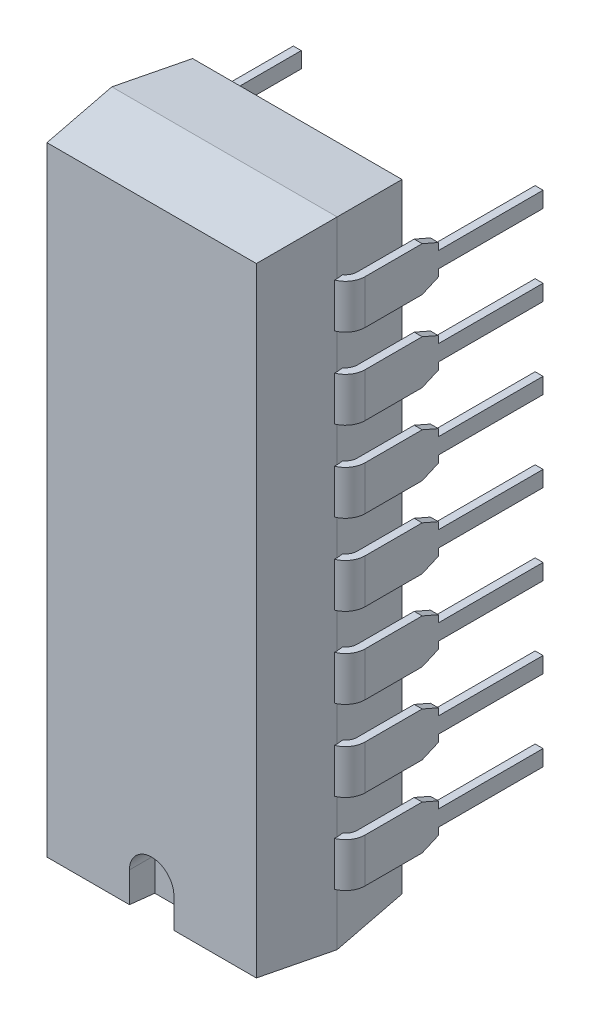
SolidWorks part; units mm, degrees
ref_plane "Plane1" through (0, 0, 0) normal (0, 0, 1) x (1, 0, 0)
ref_plane "Plane2" through (0, 0, 0) normal (0, 1, 0) x (1, 0, 0)
ref_plane "Plane3" through (0, 0, 0) normal (1, 0, 0) x (0, 0, -1)
sketch "Sketch1" plane through (0, 0, 0) normal (0, 1, 0) x (1, 0, 0)
  line L0 (-3.3, -5.1) -> (-3.55, -2.805)
  line L1 (-3.55, -2.805) -> (3.55, -2.805) construction
  line L2 (3.55, -2.805) -> (3.3, -5.1)
  line L3 (3.3, -5.1) -> (-3.3, -5.1)
  line L4 (-3.55, -2.805) -> (-3.3, -0.51)
  line L5 (-3.3, -0.51) -> (3.3, -0.51)
  line L6 (3.3, -0.51) -> (3.55, -2.805)
  line L7 (0, 0) -> (3.3, 0) construction
  line L8 (0, -0.51) -> (0, -5.1) construction
  point P11 (0, -2.805)
  point P12 (0, -5.1)
  point P13 (0, -0.51)
  dimension "D1" = 7.1
  dimension "D2" = 0.51
  dimension "D3" = 5.1
  dimension "D4" = 6.6
extrude "Basic Shape" add sketch "Sketch1" along normal mid plane 20
sketch "Sketch2" plane through (0, 0, 0) normal (1, 0, 0) x (0, 0, -1)
  line L1 (-0.51, -10) -> (-2.805, -10) construction
  line L2 (-0.51, 10) -> (-0.51, -10) construction
  line L3 (-0.51, 10) -> (-0.51, 9.75)
  line L4 (-0.51, 10) -> (-2.805, 10) construction
  line L5 (-0.51, 10) -> (-2.805, 10)
  line L6 (-2.805, 10) -> (-0.51, 9.75)
  line L7 (-0.51, -10) -> (-2.805, -10)
  line L9 (-2.805, -10) -> (-0.51, -9.75)
  line L11 (-0.51, -9.75) -> (-0.51, -10)
  dimension "D1" = 0.25
extrude "Side Profile1" cut sketch "Sketch2" against normal through all and the other way through all
sketch "Sketch3" plane through (0, 0, 0) normal (1, 0, 0) x (0, 0, -1)
  line L0 (-2.805, 10) -> (-5.1, 10) construction
  line L1 (-2.805, 10) -> (-5.1, 10)
  line L2 (-5.1, 10) -> (-5.1, -10) construction
  line L3 (-5.1, 10) -> (-5.1, 9.75)
  line L4 (-2.805, 10) -> (-5.1, 9.75)
  line L5 (-2.805, -10) -> (-5.1, -10) construction
  line L6 (-2.805, -10) -> (-5.1, -10)
  line L7 (-2.805, -10) -> (-5.1, -9.75)
  line L8 (-5.1, -9.75) -> (-5.1, -10)
extrude "Side Profile2" cut sketch "Sketch3" against normal through all and the other way through all
sketch "Sketch4" plane through (0, 0, 5.1) normal (0, 0, 1) x (1, 0, 0)
  line L2 (-0.7, -10) -> (-0.7, -8.8)
  line L3 (0.7, -8.8) -> (0.7, -10)
  line L4 (-3.55, -10) -> (3.55, -10) construction
  line L5 (-0.7, -10) -> (0.7, -10)
  arc A0 (-0.7, -8.8) -> (0.7, -8.8) centre (0, -8.8) cw
  dimension "D1" = 1.2
  dimension "D2" = 1.4
extrude "Location Mark" cut sketch "Sketch4" against normal blind 0.8
sketch "Sketch5" plane through (0, 0, 0) normal (0, 1, 0) x (1, 0, 0)
  line L0 (-3.55, -2.805) -> (3.55, -2.805) construction
  line L1 (0, -2.805) -> (3.31, -2.805)
  line L2 (3.81, -2.305) -> (3.81, 3.3)
  line L3 (3.81, -2.805) -> (-3.81, -2.805) construction
  arc A0 (3.81, -2.305) -> (3.31, -2.805) centre (3.31, -2.305) cw
  point P0 (-3.81, -2.805)
  point P8 (0, -2.805)
  dimension "D3" = 0.5
  dimension "D1" = 7.62
  dimension "D2" = 3.3
sketch "Sketch6" plane through (0, 0, 0) normal (1, 0, 0) x (0, 0, -1)
  line L0 (-2.93, 0.695) -> (-2.68, 0.695)
  line L1 (-2.93, 0.695) -> (-2.93, -0.695)
  line L2 (-2.68, -0.695) -> (-2.93, -0.695)
  line L3 (-2.68, -0.695) -> (-2.68, 0.695)
  line L4 (-2.68, 0.695) -> (-2.93, -0.695) construction
  point P4 (-2.805, 0)
  dimension "D1" = 1.39
  dimension "D2" = 0.25
sweep "Central Pin" add profiles "Sketch6" path "Sketch5"
sketch "Sketch7" plane through (3.685, 0, 0) normal (-1, 0, 0) x (0, 0, 1)
  line L0 (-3.3, -0.695) -> (-3.3, 0.695) construction
  line L1 (2.305, -0.695) -> (-3.3, -0.695) construction
  line L2 (-3.3, -0.25) -> (-3.3, 0.25) construction
  line L3 (-3.3, -0.25) -> (0, -0.25)
  line L4 (50, 0) -> (-50, 0) construction
  line L5 (-3.3, 0.25) -> (0, 0.25)
  line L6 (0, 0.25) -> (0, 0.4725)
  line L7 (0, -0.25) -> (0, -0.4725)
  line L8 (2.305, 0.695) -> (-3.3, 0.695) construction
  line L9 (0.51, 0.695) -> (-3.3, 0.695)
  line L10 (2.305, -0.695) -> (-3.3, -0.695) construction
  line L11 (0.51, -0.695) -> (-3.3, -0.695)
  line L12 (-3.3, -0.25) -> (-3.3, -0.695)
  line L13 (-3.3, 0.695) -> (-3.3, 0.25)
  line L14 (0, -0.4725) -> (0.51, -0.695)
  line L16 (0, 0.4725) -> (0.51, 0.695)
  line L17 (2.305, 0.695) -> (-3.3, 0.695) construction
  line L18 (0.51, 9.75) -> (0.51, -9.75) construction
  point P6 (-3.3, 0)
  point P10 (-3.3, 0.4725)
  dimension "D1" = 0.5
extrude "Pin Relief" cut sketch "Sketch7" against normal through all
mirror "Opp Pin" about plane through (0, 0, 0) normal (1, 0, 0) of "Pin Relief", "Central Pin"
pattern_linear "Upper Pins" count 4 spacing 2.54 along (0, -1, 0) of "Central Pin", "Opp Pin", "Pin Relief"
pattern_linear "Lower Pins" count 4 spacing 2.54 along (0, 1, 0) of "Pin Relief", "Opp Pin", "Central Pin"
sketch "Component_Outline" plane through (0, 0, 0) normal (0, 0, 1) x (1, 0, 0)
  line L0 (3.55, 10) -> (3.55, 8.315)
  line L1 (3.55, 8.315) -> (3.935, 8.315)
  line L2 (3.935, 8.315) -> (3.935, 6.925)
  line L3 (3.935, 6.925) -> (3.55, 6.925)
  line L4 (3.55, 6.925) -> (3.55, 5.775)
  line L5 (3.55, 5.775) -> (3.935, 5.775)
  line L6 (3.935, 5.775) -> (3.935, 4.385)
  line L7 (3.935, 4.385) -> (3.55, 4.385)
  line L8 (3.55, 4.385) -> (3.55, 3.235)
  line L9 (3.55, 3.235) -> (3.935, 3.235)
  line L10 (3.935, 3.235) -> (3.935, 1.845)
  line L11 (3.935, 1.845) -> (3.5287, 1.845)
  line L12 (3.5287, 1.845) -> (3.55, 0.695)
  line L13 (3.55, 0.695) -> (3.935, 0.695)
  line L14 (3.935, 0.695) -> (3.935, -0.695)
  line L15 (3.935, -0.695) -> (3.55, -0.695)
  line L16 (3.55, -0.695) -> (3.55, -1.845)
  line L17 (3.55, -1.845) -> (3.935, -1.845)
  line L18 (3.935, -1.845) -> (3.935, -3.235)
  line L19 (3.935, -3.235) -> (3.55, -3.235)
  line L20 (3.55, -3.235) -> (3.55, -4.385)
  line L21 (3.55, -4.385) -> (3.935, -4.385)
  line L22 (3.935, -4.385) -> (3.935, -5.775)
  line L23 (3.935, -5.775) -> (3.55, -5.775)
  line L24 (3.55, -5.775) -> (3.55, -6.925)
  line L25 (3.55, -6.925) -> (3.935, -6.925)
  line L26 (3.935, -6.925) -> (3.935, -8.315)
  line L27 (3.935, -8.315) -> (3.55, -8.315)
  line L28 (3.55, -8.315) -> (3.55, -10)
  line L29 (0, 10) -> (0, -10) construction
  line L30 (-3.55, 10) -> (3.55, 10) construction
  line L31 (-3.55, -10) -> (3.55, -10) construction
  line L32 (-3.55, -8.315) -> (-3.55, -10)
  line L33 (-3.935, -8.315) -> (-3.55, -8.315)
  line L34 (-3.935, -6.925) -> (-3.935, -8.315)
  line L35 (-3.55, -6.925) -> (-3.935, -6.925)
  line L36 (-3.55, -5.775) -> (-3.55, -6.925)
  line L37 (-3.935, -5.775) -> (-3.55, -5.775)
  line L38 (-3.935, -4.385) -> (-3.935, -5.775)
  line L39 (-3.55, -4.385) -> (-3.935, -4.385)
  line L40 (-3.55, -3.235) -> (-3.55, -4.385)
  line L41 (-3.935, -3.235) -> (-3.55, -3.235)
  line L42 (-3.935, -1.845) -> (-3.935, -3.235)
  line L43 (-3.55, -1.845) -> (-3.935, -1.845)
  line L44 (-3.55, -0.695) -> (-3.55, -1.845)
  line L45 (-3.935, -0.695) -> (-3.55, -0.695)
  line L46 (-3.935, 0.695) -> (-3.935, -0.695)
  line L47 (-3.55, 0.695) -> (-3.935, 0.695)
  line L48 (-3.5287, 1.845) -> (-3.55, 0.695)
  line L49 (-3.935, 1.845) -> (-3.5287, 1.845)
  line L50 (-3.935, 3.235) -> (-3.935, 1.845)
  line L51 (-3.55, 3.235) -> (-3.935, 3.235)
  line L52 (-3.55, 4.385) -> (-3.55, 3.235)
  line L53 (-3.935, 4.385) -> (-3.55, 4.385)
  line L54 (-3.935, 5.775) -> (-3.935, 4.385)
  line L55 (-3.55, 5.775) -> (-3.935, 5.775)
  line L56 (-3.55, 6.925) -> (-3.55, 5.775)
  line L57 (-3.935, 6.925) -> (-3.55, 6.925)
  line L58 (-3.935, 8.315) -> (-3.935, 6.925)
  line L59 (-3.55, 8.315) -> (-3.935, 8.315)
  line L60 (-3.55, 10) -> (-3.55, 8.315)
  line L61 (3.55, 10) -> (-3.55, 10)
  line L62 (3.55, -10) -> (-3.55, -10)
